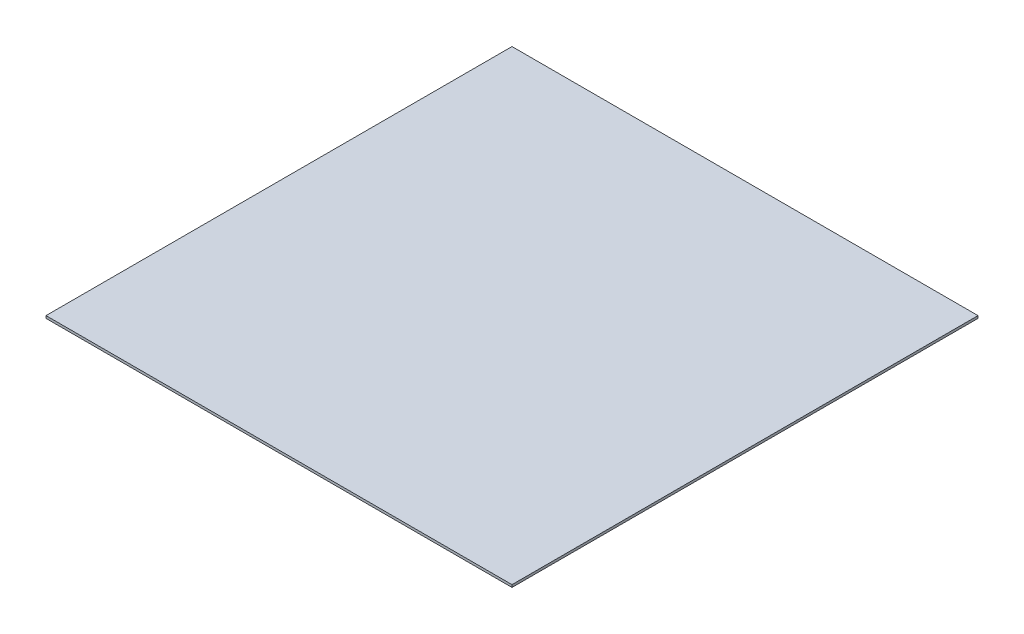
SolidWorks part; units mm, degrees
ref_plane "Front Plane" through (0, 0, 0) normal (0, 0, 1) x (1, 0, 0)
ref_plane "Top Plane" through (0, 0, 0) normal (0, 1, 0) x (1, 0, 0)
ref_plane "Right Plane" through (0, 0, 0) normal (1, 0, 0) x (0, 0, -1)
sketch "Sketch1" plane through (0, 0, 0) normal (0, 1, 0) x (1, 0, 0)
  line L1 (-38.1, -38.1) -> (38.1, -38.1)
  line L2 (-38.1, -38.1) -> (-38.1, 38.1)
  line L3 (-38.1, 38.1) -> (38.1, 38.1)
  line L4 (38.1, -38.1) -> (38.1, 38.1)
  line L5 (-38.1, -38.1) -> (38.1, 38.1) construction
  line L6 (-38.1, 38.1) -> (38.1, -38.1) construction
  point P1 (0, 0)
  dimension "D1" = 76.2
extrude "Boss-Extrude1" add sketch "Sketch1" along normal blind 0.4
